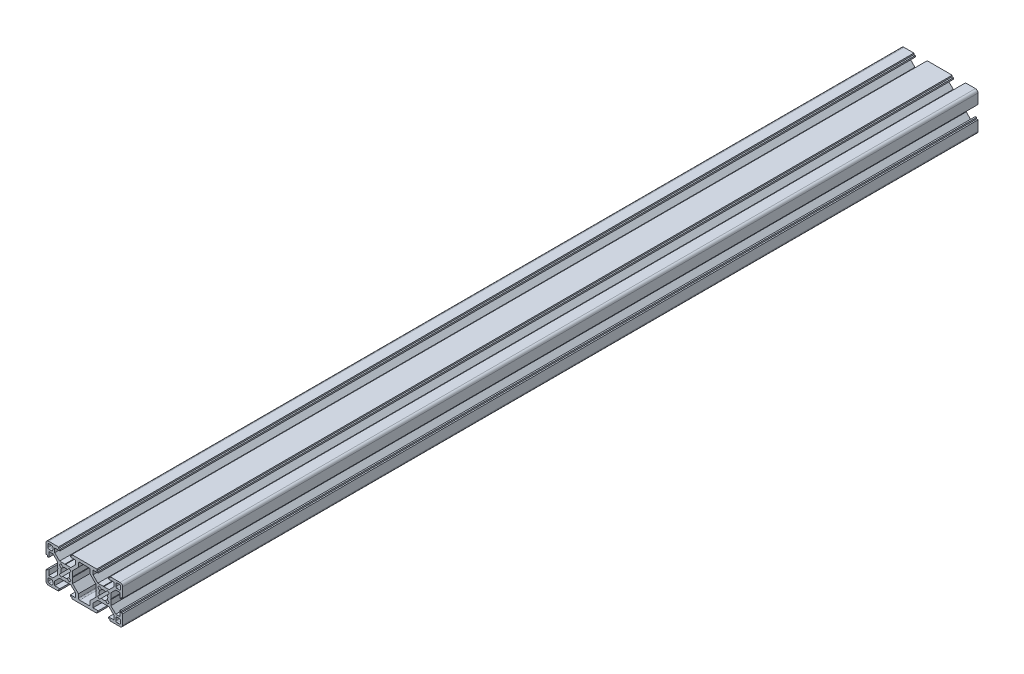
SolidWorks part; units mm, degrees
material "3003 Alloy"
ref_plane "Frente" through (0, 0, 0) normal (0, 0, 1) x (1, 0, 0)
ref_plane "Topo" through (0, 0, 0) normal (0, 1, 0) x (1, 0, 0)
ref_plane "Lateral" through (0, 0, 0) normal (1, 0, 0) x (0, 0, -1)
sketch "Sketch1" plane through (0, 0, 0) normal (0, 0, 1) x (1, 0, 0)
  line L0 (-28.5, 10.7) -> (-28.5, 12.5)
  line L1 (-27.5, 13.5) -> (-25.7, 13.5)
  line L2 (-24.7, 12.5) -> (-24.7, 10.7)
  line L3 (-25.7, 9.7) -> (-27.5, 9.7)
  line L4 (-11.9951, -1.5907) -> (-10.4041, -3.1817)
  line L5 (-10.4041, -3.1817) -> (-11.8183, -4.5959)
  line L6 (-11.8183, -4.5959) -> (-13.4093, -3.0049)
  line L7 (-16.5907, -3.0049) -> (-18.1817, -4.5959)
  line L8 (-18.1817, -4.5959) -> (-19.5959, -3.1817)
  line L9 (-19.5959, -3.1817) -> (-18.0049, -1.5907)
  line L10 (-18.0049, 1.5907) -> (-19.5959, 3.1817)
  line L11 (-19.5959, 3.1817) -> (-18.1817, 4.5959)
  line L12 (-18.1817, 4.5959) -> (-16.5907, 3.0049)
  line L13 (-13.4093, 3.0049) -> (-11.8183, 4.5959)
  line L14 (-11.8183, 4.5959) -> (-10.4041, 3.1817)
  line L15 (-10.4041, 3.1817) -> (-11.9951, 1.5907)
  line L16 (-28.5, -12.5) -> (-28.5, -10.7)
  line L17 (-27.5, -9.7) -> (-25.7, -9.7)
  line L18 (-24.7, -10.7) -> (-24.7, -12.5)
  line L19 (-25.7, -13.5) -> (-27.5, -13.5)
  line L20 (28.5, -10.7) -> (28.5, -12.5)
  line L21 (27.5, -13.5) -> (25.7, -13.5)
  line L22 (24.7, -12.5) -> (24.7, -10.7)
  line L23 (25.7, -9.7) -> (27.5, -9.7)
  line L24 (11.9951, 1.5907) -> (10.4041, 3.1817)
  line L25 (10.4041, 3.1817) -> (11.8183, 4.5959)
  line L26 (11.8183, 4.5959) -> (13.4093, 3.0049)
  line L27 (16.5907, 3.0049) -> (18.1817, 4.5959)
  line L28 (18.1817, 4.5959) -> (19.5959, 3.1817)
  line L29 (19.5959, 3.1817) -> (18.0049, 1.5907)
  line L30 (18.0049, -1.5907) -> (19.5959, -3.1817)
  line L31 (19.5959, -3.1817) -> (18.1817, -4.5959)
  line L32 (18.1817, -4.5959) -> (16.5907, -3.0049)
  line L33 (13.4093, -3.0049) -> (11.8183, -4.5959)
  line L34 (11.8183, -4.5959) -> (10.4041, -3.1817)
  line L35 (10.4041, -3.1817) -> (11.9951, -1.5907)
  line L36 (28.5, 12.5) -> (28.5, 10.7)
  line L37 (27.5, 9.7) -> (25.7, 9.7)
  line L38 (24.7, 10.7) -> (24.7, 12.5)
  line L39 (25.7, 13.5) -> (27.5, 13.5)
  line L40 (3.6, -12.8) -> (-3.6, -12.8)
  line L41 (-4.6, -11.8) -> (-4.6, -8.9858)
  line L42 (-4.6, -8.9858) -> (-9.2, -4.3858)
  line L43 (-9.2, -4.3858) -> (-9.2, -0.25)
  line L44 (-9.2, -0.25) -> (-9.45, 0)
  line L45 (-9.45, 0) -> (-9.2, 0.25)
  line L46 (-9.2, 0.25) -> (-9.2, 4.3858)
  line L47 (-9.2, 4.3858) -> (-4.6, 8.9858)
  line L48 (-4.6, 8.9858) -> (-4.6, 11.8)
  line L49 (-3.6, 12.8) -> (3.6, 12.8)
  line L50 (4.6, 11.8) -> (4.6, 8.9858)
  line L51 (4.6, 8.9858) -> (9.2, 4.3858)
  line L52 (9.2, 4.3858) -> (9.2, 0.25)
  line L53 (9.2, 0.25) -> (9.45, 0)
  line L54 (9.45, 0) -> (9.2, -0.25)
  line L55 (9.2, -0.25) -> (9.2, -4.3858)
  line L56 (9.2, -4.3858) -> (4.6, -8.9858)
  line L57 (4.6, -8.9858) -> (4.6, -11.8)
  line L58 (-9.8, -15) -> (9.8, -15)
  line L59 (9.8, -15) -> (9.8, -13.9)
  line L60 (9.8, -13.9) -> (10.9, -13.9)
  line L61 (10.9, -13.9) -> (10.9, -12.8)
  line L62 (10.9, -12.8) -> (6.8, -12.8)
  line L63 (6.8, -12.8) -> (6.8, -9.6142)
  line L64 (6.8, -9.6142) -> (10.6142, -5.8)
  line L65 (10.6142, -5.8) -> (14.75, -5.8)
  line L66 (14.75, -5.8) -> (15, -5.55)
  line L67 (15, -5.55) -> (15.25, -5.8)
  line L68 (15.25, -5.8) -> (19.3858, -5.8)
  line L69 (19.3858, -5.8) -> (23.2, -9.6142)
  line L70 (23.2, -9.6142) -> (23.2, -12.8)
  line L71 (23.2, -12.8) -> (19.1, -12.8)
  line L72 (19.1, -12.8) -> (19.1, -13.9)
  line L73 (19.1, -13.9) -> (20.2, -13.9)
  line L74 (20.2, -13.9) -> (20.2, -15)
  line L75 (20.2, -15) -> (28, -15)
  line L76 (30, -13) -> (30, -5.2)
  line L77 (30, -5.2) -> (28.9, -5.2)
  line L78 (28.9, -5.2) -> (28.9, -4.1)
  line L79 (28.9, -4.1) -> (27.8, -4.1)
  line L80 (27.8, -4.1) -> (27.8, -8.2)
  line L81 (27.8, -8.2) -> (24.6142, -8.2)
  line L82 (24.6142, -8.2) -> (20.8, -4.3858)
  line L83 (20.8, -4.3858) -> (20.8, -0.25)
  line L84 (20.8, -0.25) -> (20.55, 0)
  line L85 (20.55, 0) -> (20.8, 0.25)
  line L86 (20.8, 0.25) -> (20.8, 4.3858)
  line L87 (20.8, 4.3858) -> (24.6142, 8.2)
  line L88 (24.6142, 8.2) -> (27.8, 8.2)
  line L89 (27.8, 8.2) -> (27.8, 4.1)
  line L90 (27.8, 4.1) -> (28.9, 4.1)
  line L91 (28.9, 4.1) -> (28.9, 5.2)
  line L92 (28.9, 5.2) -> (30, 5.2)
  line L93 (30, 5.2) -> (30, 13)
  line L94 (28, 15) -> (20.2, 15)
  line L95 (20.2, 15) -> (20.2, 13.9)
  line L96 (20.2, 13.9) -> (19.1, 13.9)
  line L97 (19.1, 13.9) -> (19.1, 12.8)
  line L98 (19.1, 12.8) -> (23.2, 12.8)
  line L99 (23.2, 12.8) -> (23.2, 9.6142)
  line L100 (23.2, 9.6142) -> (19.3858, 5.8)
  line L101 (19.3858, 5.8) -> (15.25, 5.8)
  line L102 (15.25, 5.8) -> (15, 5.55)
  line L103 (15, 5.55) -> (14.75, 5.8)
  line L104 (14.75, 5.8) -> (10.6142, 5.8)
  line L105 (10.6142, 5.8) -> (6.8, 9.6142)
  line L106 (6.8, 9.6142) -> (6.8, 12.8)
  line L107 (6.8, 12.8) -> (10.9, 12.8)
  line L108 (10.9, 12.8) -> (10.9, 13.9)
  line L109 (10.9, 13.9) -> (9.8, 13.9)
  line L110 (9.8, 13.9) -> (9.8, 15)
  line L111 (9.8, 15) -> (-9.8, 15)
  line L112 (-9.8, 15) -> (-9.8, 13.9)
  line L113 (-9.8, 13.9) -> (-10.9, 13.9)
  line L114 (-10.9, 13.9) -> (-10.9, 12.8)
  line L115 (-10.9, 12.8) -> (-6.8, 12.8)
  line L116 (-6.8, 12.8) -> (-6.8, 9.6142)
  line L117 (-6.8, 9.6142) -> (-10.6142, 5.8)
  line L118 (-10.6142, 5.8) -> (-14.75, 5.8)
  line L119 (-14.75, 5.8) -> (-15, 5.55)
  line L120 (-15, 5.55) -> (-15.25, 5.8)
  line L121 (-15.25, 5.8) -> (-19.3858, 5.8)
  line L122 (-19.3858, 5.8) -> (-23.2, 9.6142)
  line L123 (-23.2, 9.6142) -> (-23.2, 12.8)
  line L124 (-23.2, 12.8) -> (-19.1, 12.8)
  line L125 (-19.1, 12.8) -> (-19.1, 13.9)
  line L126 (-19.1, 13.9) -> (-20.2, 13.9)
  line L127 (-20.2, 13.9) -> (-20.2, 15)
  line L128 (-20.2, 15) -> (-28, 15)
  line L129 (-30, 13) -> (-30, 5.2)
  line L130 (-30, 5.2) -> (-28.9, 5.2)
  line L131 (-28.9, 5.2) -> (-28.9, 4.1)
  line L132 (-28.9, 4.1) -> (-27.8, 4.1)
  line L133 (-27.8, 4.1) -> (-27.8, 8.2)
  line L134 (-27.8, 8.2) -> (-24.6142, 8.2)
  line L135 (-24.6142, 8.2) -> (-20.8, 4.3858)
  line L136 (-20.8, 4.3858) -> (-20.8, 0.25)
  line L137 (-20.8, 0.25) -> (-20.55, 0)
  line L138 (-20.55, 0) -> (-20.8, -0.25)
  line L139 (-20.8, -0.25) -> (-20.8, -4.3858)
  line L140 (-20.8, -4.3858) -> (-24.6142, -8.2)
  line L141 (-24.6142, -8.2) -> (-27.8, -8.2)
  line L142 (-27.8, -8.2) -> (-27.8, -4.1)
  line L143 (-27.8, -4.1) -> (-28.9, -4.1)
  line L144 (-28.9, -4.1) -> (-28.9, -5.2)
  line L145 (-28.9, -5.2) -> (-30, -5.2)
  line L146 (-30, -5.2) -> (-30, -13)
  line L147 (-28, -15) -> (-20.2, -15)
  line L148 (-20.2, -15) -> (-20.2, -13.9)
  line L149 (-20.2, -13.9) -> (-19.1, -13.9)
  line L150 (-19.1, -13.9) -> (-19.1, -12.8)
  line L151 (-19.1, -12.8) -> (-23.2, -12.8)
  line L152 (-23.2, -12.8) -> (-23.2, -9.6142)
  line L153 (-23.2, -9.6142) -> (-19.3858, -5.8)
  line L154 (-19.3858, -5.8) -> (-15.25, -5.8)
  line L155 (-15.25, -5.8) -> (-15, -5.55)
  line L156 (-15, -5.55) -> (-14.75, -5.8)
  line L157 (-14.75, -5.8) -> (-10.6142, -5.8)
  line L158 (-10.6142, -5.8) -> (-6.8, -9.6142)
  line L159 (-6.8, -9.6142) -> (-6.8, -12.8)
  line L160 (-6.8, -12.8) -> (-10.9, -12.8)
  line L161 (-10.9, -12.8) -> (-10.9, -13.9)
  line L162 (-10.9, -13.9) -> (-9.8, -13.9)
  line L163 (-9.8, -13.9) -> (-9.8, -15)
  arc A0 (-28.5, 12.5) -> (-27.5, 13.5) centre (-27.5, 12.5) cw
  arc A1 (-25.7, 13.5) -> (-24.7, 12.5) centre (-25.7, 12.5) cw
  arc A2 (-24.7, 10.7) -> (-25.7, 9.7) centre (-25.7, 10.7) cw
  arc A3 (-27.5, 9.7) -> (-28.5, 10.7) centre (-27.5, 10.7) cw
  arc A4 (-11.9951, 1.5907) -> (-11.9951, -1.5907) centre (-15, 0) cw
  arc A5 (-13.4093, -3.0049) -> (-16.5907, -3.0049) centre (-15, 0) cw
  arc A6 (-18.0049, -1.5907) -> (-18.0049, 1.5907) centre (-15, 0) cw
  arc A7 (-16.5907, 3.0049) -> (-13.4093, 3.0049) centre (-15, 0) cw
  arc A8 (-28.5, -10.7) -> (-27.5, -9.7) centre (-27.5, -10.7) cw
  arc A9 (-25.7, -9.7) -> (-24.7, -10.7) centre (-25.7, -10.7) cw
  arc A10 (-24.7, -12.5) -> (-25.7, -13.5) centre (-25.7, -12.5) cw
  arc A11 (-27.5, -13.5) -> (-28.5, -12.5) centre (-27.5, -12.5) cw
  arc A12 (28.5, -12.5) -> (27.5, -13.5) centre (27.5, -12.5) cw
  arc A13 (25.7, -13.5) -> (24.7, -12.5) centre (25.7, -12.5) cw
  arc A14 (24.7, -10.7) -> (25.7, -9.7) centre (25.7, -10.7) cw
  arc A15 (27.5, -9.7) -> (28.5, -10.7) centre (27.5, -10.7) cw
  arc A16 (11.9951, -1.5907) -> (11.9951, 1.5907) centre (15, 0) cw
  arc A17 (13.4093, 3.0049) -> (16.5907, 3.0049) centre (15, 0) cw
  arc A18 (18.0049, 1.5907) -> (18.0049, -1.5907) centre (15, 0) cw
  arc A19 (16.5907, -3.0049) -> (13.4093, -3.0049) centre (15, 0) cw
  arc A20 (28.5, 10.7) -> (27.5, 9.7) centre (27.5, 10.7) cw
  arc A21 (25.7, 9.7) -> (24.7, 10.7) centre (25.7, 10.7) cw
  arc A22 (24.7, 12.5) -> (25.7, 13.5) centre (25.7, 12.5) cw
  arc A23 (27.5, 13.5) -> (28.5, 12.5) centre (27.5, 12.5) cw
  arc A24 (-3.6, -12.8) -> (-4.6, -11.8) centre (-3.6, -11.8) cw
  arc A25 (-4.6, 11.8) -> (-3.6, 12.8) centre (-3.6, 11.8) cw
  arc A26 (3.6, 12.8) -> (4.6, 11.8) centre (3.6, 11.8) cw
  arc A27 (4.6, -11.8) -> (3.6, -12.8) centre (3.6, -11.8) cw
  arc A28 (28, -15) -> (30, -13) centre (28, -13) ccw
  arc A29 (30, 13) -> (28, 15) centre (28, 13) ccw
  arc A30 (-28, 15) -> (-30, 13) centre (-28, 13) ccw
  arc A31 (-30, -13) -> (-28, -15) centre (-28, -13) ccw
extrude "Boss-Extrude1" add sketch "Sketch1" against normal mid plane 670
